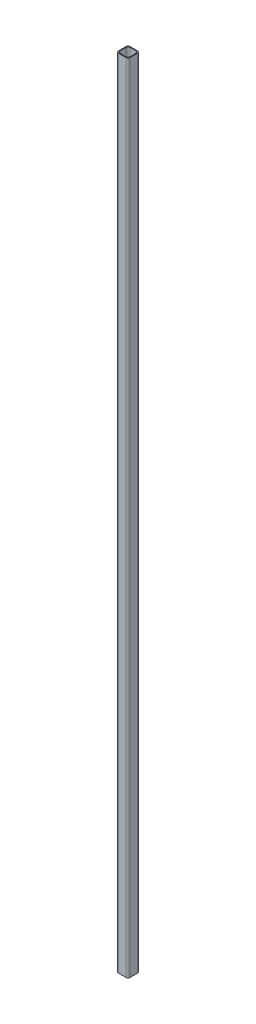
SolidWorks part; units mm, degrees
ref_plane "Спереди" through (0, 0, 0) normal (0, 0, 1) x (1, 0, 0)
ref_plane "Сверху" through (0, 0, 0) normal (0, 1, 0) x (1, 0, 0)
ref_plane "Справа" through (0, 0, 0) normal (1, 0, 0) x (0, 0, -1)
sketch "Эскиз1" plane through (0, 0, 0) normal (0, 1, 0) x (1, 0, 0)
  line L1 (-20, 30) -> (20, 30)
  line L2 (-30, 20) -> (-30, -20)
  line L3 (-20, -30) -> (20, -30)
  line L4 (30, 20) -> (30, -20)
  line L5 (-30, 30) -> (30, -30) construction
  line L6 (-30, -30) -> (30, 30) construction
  line L7 (-16, 26) -> (16, 26)
  line L8 (-26, 16) -> (-26, -16)
  line L9 (-16, -26) -> (16, -26)
  line L10 (26, 16) -> (26, -16)
  line L11 (-26, 26) -> (26, -26) construction
  line L12 (-26, -26) -> (26, 26) construction
  arc A0 (20, 30) -> (30, 20) centre (20, 20) cw
  arc A1 (-20, 30) -> (-30, 20) centre (-20, 20) ccw
  arc A2 (-30, -20) -> (-20, -30) centre (-20, -20) ccw
  arc A3 (20, -30) -> (30, -20) centre (20, -20) ccw
  arc A4 (16, -26) -> (26, -16) centre (16, -16) ccw
  arc A5 (16, 26) -> (26, 16) centre (16, 16) cw
  arc A6 (-16, 26) -> (-26, 16) centre (-16, 16) ccw
  arc A7 (-26, -16) -> (-16, -26) centre (-16, -16) ccw
  point P0 (0, 0)
  point P6 (0, 0)
  dimension "D5" = 10
  dimension "D1" = 60
  dimension "D2" = 60
  dimension "D3" = 4
  dimension "D4" = 4
extrude "Бобышка-Вытянуть1" add sketch "Эскиз1" along normal blind 4120
